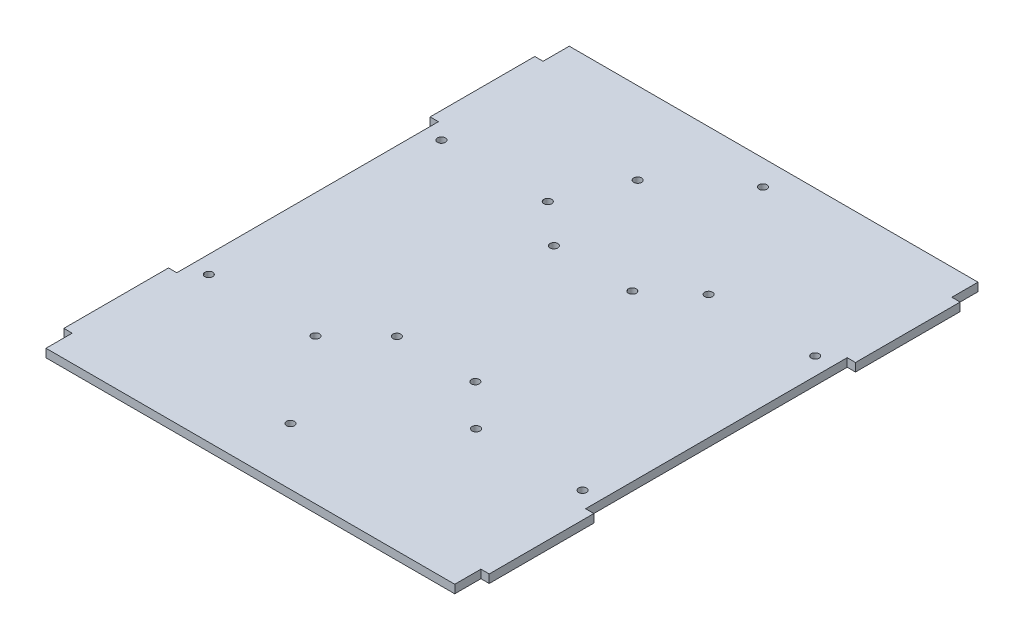
SolidWorks part; units mm, degrees
ref_plane "Front Plane" through (0, 0, 0) normal (0, 0, 1) x (1, 0, 0)
ref_plane "Top Plane" through (0, 0, 0) normal (0, 1, 0) x (1, 0, 0)
ref_plane "Right Plane" through (0, 0, 0) normal (1, 0, 0) x (0, 0, -1)
sketch "Sketch1" plane through (0, 0, 0) normal (0, 1, 0) x (1, 0, 0)
  line L0 (0, 190) -> (-3.175, 190)
  line L1 (0, 0) -> (156.24, 0)
  line L2 (0, 200) -> (0, 190)
  line L3 (0, 200) -> (156.24, 200)
  line L4 (156.24, 200) -> (156.24, 190)
  line L5 (-3.175, 190) -> (-3.175, 150)
  line L6 (-3.175, 150) -> (0, 150)
  line L7 (0, 150) -> (0, 50)
  line L8 (156.24, 190) -> (159.415, 190)
  line L9 (159.415, 190) -> (159.415, 150)
  line L10 (159.415, 150) -> (156.24, 150)
  line L11 (156.24, 150) -> (156.24, 50)
  line L12 (0, 10) -> (-3.175, 10)
  line L13 (-3.175, 10) -> (-3.175, 50)
  line L14 (-3.175, 50) -> (0, 50)
  line L15 (156.24, 10) -> (159.415, 10)
  line L16 (159.415, 10) -> (159.415, 50)
  line L17 (159.415, 50) -> (156.24, 50)
  line L18 (0, 10) -> (0, 0)
  line L19 (156.24, 10) -> (156.24, 0)
  point P21 (6.6875, 144.455)
  point P22 (47.4175, 144.455)
  point P23 (6.6875, 55.545)
  point P24 (47.4175, 55.545)
  point P25 (108.8225, 144.455)
  point P26 (149.5525, 144.455)
  point P27 (149.5525, 55.545)
  point P28 (108.8225, 55.545)
  point P29 (62.71, 130.2405)
  point P30 (93.63, 130.2405)
  point P31 (57.438, 168.72)
  point P32 (83.63, 190.4)
  point P33 (62.71, 72.0195)
  point P34 (93.63, 72.0195)
  point P35 (71.62, 21.8)
  dimension "D1" = 200
  dimension "D2" = 156.24
  dimension "D3" = 10
  dimension "D4" = 40
  dimension "D5" = 3.175
  dimension "D6" = 3.175
  dimension "D7" = 40
  dimension "D8" = 10
  dimension "D9" = 40
  dimension "D10" = 10
  dimension "D11" = 3.175
  dimension "D12" = 3.175
  dimension "D13" = 3.175
  dimension "D14" = 40
  dimension "D15" = 3.175
  dimension "D16" = 3.175
  dimension "D17" = 3.175
  dimension "D18" = 57.438
  dimension "D19" = 31.28
  dimension "D20" = 9.6
  dimension "D21" = 83.63
  dimension "D22" = 6.6875
  dimension "D23" = 55.545
  dimension "D24" = 47.4175
  dimension "D25" = 55.545
  dimension "D26" = 6.6875
  dimension "D27" = 47.4175
  dimension "D28" = 69.7595
  dimension "D29" = 72.0195
  dimension "D30" = 62.71
  dimension "D31" = 62.61
  dimension "D32" = 71.62
  dimension "D33" = 21.8
extrude "Boss-Extrude1" add sketch "Sketch1" along normal blind 3.175
hole_wizard "Ø1.0 (1) Diameter Hole1" positions "Sketch3" profile "Sketch2" hole size "Ø1.0" standard "ANSI Metric" end condition through all
sketch "Sketch3" plane through (0, 3.175, 0) normal (0, 1, 0) x (1, 0, 0)
  point P2 (47.3275, 144.4675)
  point P4 (6.6821, 144.4675)
  point P6 (57.427, 168.7268)
  point P8 (83.6296, 190.4009)
  point P10 (108.8222, 144.4542)
  point P14 (149.552, 144.4542)
  point P20 (47.4175, 55.545)
  point P22 (108.8225, 55.545)
  point P24 (149.5525, 55.545)
  point P26 (71.62, 21.8)
  point P28 (6.6875, 55.545)
sketch "Sketch2" plane through (47.3275, 3.175, -144.4675) normal (1, 0, 0) x (0, 0, 1)
  line L0 (0, 0) -> (0, 3.175)
  line L1 (0, 3.175) -> (1.5, 3.175)
  line L2 (1.5, 3.175) -> (1.5, 0)
  line L5 (1.5, 0) -> (0, 0)
  line L11 (0, -6.35) -> (0, 107.95) construction
  dimension "Thru Hole Dia." = 3
  dimension "Thru Hole Depth" = 3.175
hole_wizard "Ø3.0 (3) Diameter Hole1" positions "Sketch7" profile "Sketch5" hole size "Ø3.0" standard "ANSI Metric" end condition through all
sketch "Sketch7" plane through (0, 3.175, 0) normal (0, 1, 0) x (1, 0, 0)
  point P9 (63.1213, 131.0004)
  point P12 (93.12, 131)
  point P15 (63.1213, 71.0004)
  point P18 (93.12, 71)
sketch "Sketch5" plane through (63.1213, 3.175, -131.0004) normal (1, 0, 0) x (0, 0, 1)
  line L0 (0, 0) -> (0, 3.175)
  line L1 (0, 3.175) -> (1.5, 3.175)
  line L2 (1.5, 3.175) -> (1.5, 0)
  line L5 (1.5, 0) -> (0, 0)
  line L11 (0, -6.35) -> (0, 107.95) construction
  dimension "Thru Hole Dia." = 3
  dimension "Thru Hole Depth" = 3.175
